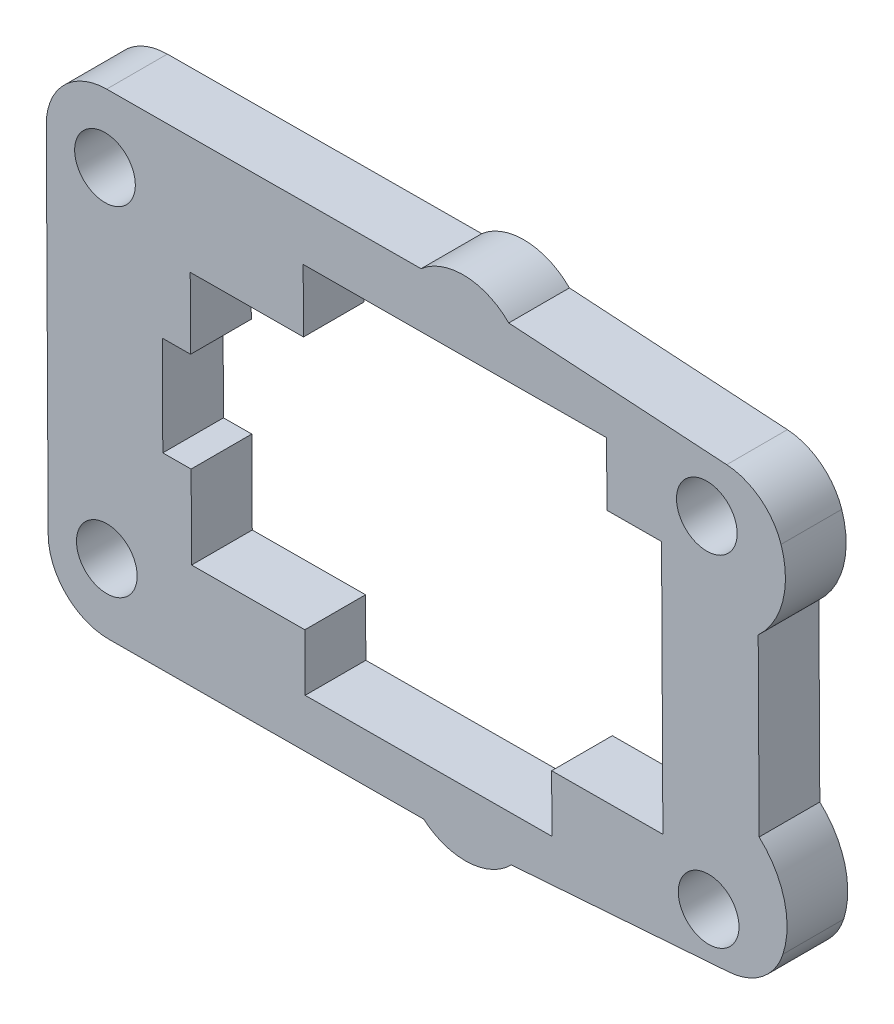
SolidWorks part; units mm, degrees
ref_plane "Front Plane" through (0, 0, 0) normal (0, 0, 1) x (1, 0, 0)
ref_plane "Top Plane" through (0, 0, 0) normal (0, 1, 0) x (1, 0, 0)
ref_plane "Right Plane" through (0, 0, 0) normal (1, 0, 0) x (0, 0, -1)
sketch "Sketch1" plane through (0, 0, 0) normal (0, 0, 1) x (1, 0, 0)
  line L0 (-3, 8.75) -> (39.4671, 8.75) construction
  line L25 (15.4351, 20.9214) -> (-0.1087, 20.8382)
  line L26 (-3.0926, 17.8222) -> (-2.999, 0.3224)
  line L27 (0.0171, -2.6615) -> (15.5608, -2.5783)
  line L28 (19.8915, -2.3745) -> (30.6595, -1.5803)
  line L29 (32.1461, 4.9453) -> (32.0999, 13.5757)
  line L30 (30.5435, 20.0851) -> (19.7676, 20.764)
  line L89 (2.641, 11.5528) -> (2.6672, 6.6528)
  line L90 (4.041, 11.5603) -> (2.641, 11.5528)
  line L91 (4.0223, 15.0602) -> (4.041, 11.5603)
  line L92 (9.6222, 15.0902) -> (4.0223, 15.0602)
  line L93 (9.6056, 18.1901) -> (9.6222, 15.0902)
  line L94 (24.6054, 18.2704) -> (9.6056, 18.1901)
  line L95 (24.622, 15.1705) -> (24.6054, 18.2704)
  line L96 (27.3219, 15.1849) -> (24.622, 15.1705)
  line L97 (27.3888, 2.6851) -> (27.3219, 15.1849)
  line L98 (21.8889, 2.6557) -> (27.3888, 2.6851)
  line L99 (21.9039, -0.1443) -> (21.8889, 2.6557)
  line L100 (9.7041, -0.2096) -> (21.9039, -0.1443)
  line L101 (9.6891, 2.5904) -> (9.7041, -0.2096)
  line L102 (4.0892, 2.5604) -> (9.6891, 2.5904)
  line L103 (4.0672, 6.6603) -> (4.0892, 2.5604)
  line L104 (2.6672, 6.6528) -> (4.0672, 6.6603)
  circle A11 centre (29.5602, 17.3921) radius 1.5
  circle A13 centre (29.65, 0.6048) radius 1.5
  circle A15 centre (-0.1011, 0.7379) radius 1.5
  arc A34 (19.7676, 20.764) -> (15.4351, 20.9214) centre (17.5174, 18.5325) ccw
  arc A35 (-0.1087, 20.8382) -> (-3.0926, 17.8222) centre (-0.0926, 17.8382) ccw
  arc A36 (-2.999, 0.3224) -> (0.0171, -2.6615) centre (0.001, 0.3385) ccw
  arc A37 (15.5608, -2.5783) -> (19.8915, -2.3745) centre (17.6175, -0.1672) ccw
  arc A38 (30.6595, -1.5803) -> (33.3237, 0.5166) centre (30.4364, 1.4441) ccw
  arc A39 (33.3237, 0.5166) -> (32.1461, 4.9453) centre (29.2856, 1.8138) ccw
  arc A40 (32.0999, 13.5757) -> (33.23, 18.0168) centre (29.206, 16.6765) ccw
  arc A41 (33.23, 18.0168) -> (30.5435, 20.0851) centre (30.3528, 17.0584) ccw
  circle A42 centre (-0.1905, 17.4377) radius 1.5
  dimension "D7" = 4.8999
  dimension "D9" = 4.0999
  dimension "D10" = 2.8
  dimension "D12" = 14.9998
  dimension "D14" = 5.4999
  dimension "D31" = 3
  dimension "D21" = 4.2414
  dimension "D22" = 3.0326
  dimension "D23" = 3
  dimension "D25" = 3.1691
  dimension "D27" = 3
  dimension "D28" = 3
  dimension "D30" = 3
  dimension "D33" = 3.1691
  dimension "D34" = 4.2414
  dimension "D35" = 3.0326
  dimension "D36" = 3
  dimension "D5" = 12.1998
  dimension "D8" = 3.4999
  dimension "D11" = 3.1
  dimension "D15" = 5.5999
  dimension "D16" = 1.4
  dimension "D17" = 5.5999
  dimension "D18" = 2.7
  dimension "D19" = 12.4998
  dimension "D20" = 8.6304
  dimension "D24" = 10.7972
  dimension "D26" = 15.5438
  dimension "D29" = 17.4997
  dimension "D32" = 15.5438
  dimension "D37" = 10.7972
  dimension "D38" = 2.4
  dimension "D39" = 5.7
  dimension "D40" = 4.95
  dimension "D41" = 2.1952
  dimension "D42" = 7.75
  dimension "D43" = 2.0924
  dimension "D44" = 9.8
  dimension "D45" = 1.8
  dimension "D46" = 2.4
  dimension "D47" = 9.8
extrude "Boss-Extrude1" add sketch "Sketch1" along normal blind 3
